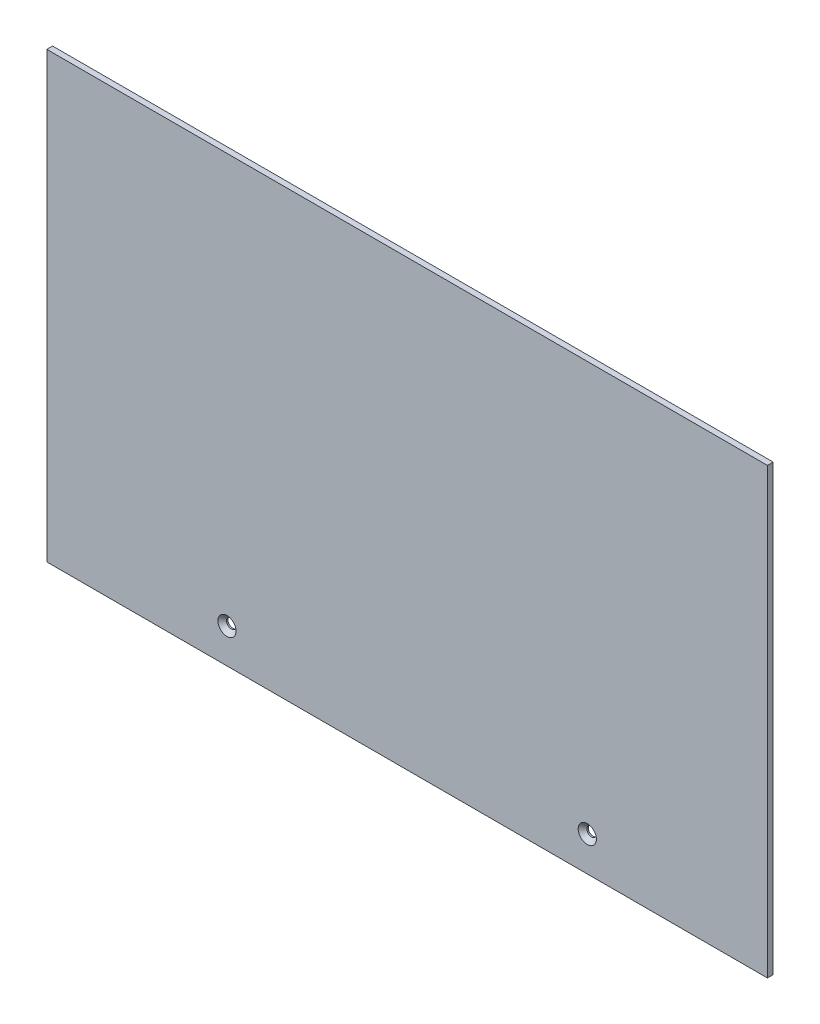
SolidWorks part; units mm, degrees
ref_plane "Front Plane" through (0, 0, 0) normal (0, 0, 1) x (1, 0, 0)
ref_plane "Top Plane" through (0, 0, 0) normal (0, 1, 0) x (1, 0, 0)
ref_plane "Right Plane" through (0, 0, 0) normal (1, 0, 0) x (0, 0, -1)
sketch "Sketch1" plane through (0, 0, 0) normal (0, 0, 1) x (1, 0, 0)
  line L1 (250, 308) -> (-250, 308)
  line L2 (250, 308) -> (250, 0)
  line L3 (250, 0) -> (-250, 0)
  line L4 (-250, 308) -> (-250, 0)
  line L5 (250, 308) -> (-250, 0) construction
  line L6 (250, 0) -> (-250, 308) construction
  point P0 (0, 154)
  point P95 (0, 0)
  dimension "D1" = 500
  dimension "D2" = 308
extrude "Boss-Extrude1" add sketch "Sketch1" along normal mid plane 4
sketch "Sketch2" plane through (0, 0, 2) normal (0, 0, 1) x (1, 0, 0)
  line L0 (0, 342.0038) -> (0, -41.8441) construction
  line L1 (-199.6009, 24) -> (202.541, 24) construction
  line L2 (-250, 0) -> (250, 0) construction
  line L3 (-250, 308) -> (-250, 0) construction
  point P7 (-125, 24)
  point P12 (125, 24)
  point P13 (0, 0)
  point P14 (0, 0)
  dimension "D1" = 24
  dimension "D3" = 125
hole_wizard "CSK for M6 Countersunk Flat Head Screw2" positions "Sketch5" profile "Sketch6" countersink size "M6" standard "ISO" end condition through all
sketch "Sketch5" plane through (0, 0, 2) normal (0, 0, 1) x (1, 0, 0)
  point P0 (-125, 24)
  point P6 (125, 24)
sketch "Sketch6" plane through (-125, 24, 2) normal (1, 0, 0) x (0, -1, 0)
  line L0 (0, 0) -> (0, 4)
  line L1 (0, 4) -> (3.3, 4)
  line L2 (3.3, 4) -> (3.3, 3)
  line L3 (3.3, 3) -> (6.3, 0)
  line L5 (6.3, 0) -> (0, 0)
  line L6 (-3.3, 3) -> (-6.3, 0) construction
  line L11 (0, -6.35) -> (0, 107.95) construction
  dimension "Thru Hole Dia." = 6.6
  dimension "Thru Hole Depth" = 4
  dimension "Near C'Sink Dia." = 12.6
  dimension "Near C'Sink Angle" = 90
